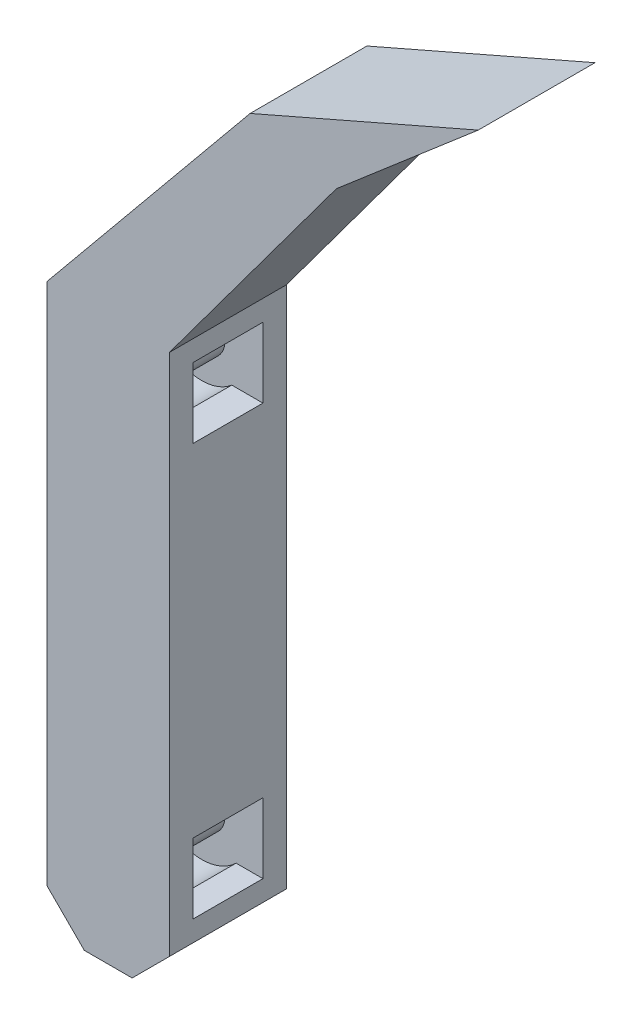
SolidWorks part; units mm, degrees
ref_plane "前视基准面" through (0, 0, 0) normal (0, 0, 1) x (1, 0, 0)
ref_plane "上视基准面" through (0, 0, 0) normal (0, 1, 0) x (1, 0, 0)
ref_plane "右视基准面" through (0, 0, 0) normal (1, 0, 0) x (0, 0, -1)
sketch "草图1" plane through (0, 0, 0) normal (0, 0, 1) x (1, 0, 0)
  line L0 (-9.5511, 87.4533) -> (33.9443, 140.3649)
  line L1 (-9.5511, 87.4533) -> (16.6885, 87.4533)
  line L2 (-9.5511, 87.4533) -> (-9.5511, -32.5467)
  line L3 (-9.5511, -32.5467) -> (16.6885, -32.5467)
  line L4 (16.6885, 87.4533) -> (16.6885, -32.5467)
  line L7 (33.9443, 140.3649) -> (82.784, 161.6933)
  line L8 (82.784, 161.6933) -> (52.4218, 135.6522)
  line L9 (52.4218, 135.6522) -> (16.6885, 87.4533)
  point P0 (0, 0)
  point P5 (0, 0)
  point P10 (0, 0)
  point P11 (82.784, 161.6933)
  point P12 (-84.1725, 179.7601)
  dimension "D1" = 120
  dimension "D2" = 60
  dimension "D3" = 40
extrude "凸台-拉伸1" add sketch "草图1" along normal blind 25 contours L4 L1 L2 L3 | L9 L8 L7 L0 L1
chamfer "倒角1" distance 8 angle 45 2 edges at (16.6885, -32.5467, 12.5) (-9.5511, -32.5467, 12.5)
sketch "草图3" plane through (-9.5511, 0, 0) normal (-1, 0, 0) x (0, 0, 1)
  line L1 (5, -5.1272) -> (20, -5.1272)
  line L2 (5, -5.1272) -> (5, -20.1272)
  line L3 (5, -20.1272) -> (20, -20.1272)
  line L4 (20, -5.1272) -> (20, -20.1272)
  line L5 (5, -5.1272) -> (20, -20.1272) construction
  line L6 (5, -20.1272) -> (20, -5.1272) construction
extrude "切除-拉伸4" cut sketch "草图3" against normal blind 35
sketch "草图4" plane through (0, 0, 5) normal (0, 0, 1) x (1, 0, 0)
  line L0 (-9.5511, -5.1272) -> (16.6885, -20.1272)
  line L1 (16.6885, -5.1272) -> (-9.5511, -20.1272)
  line L4 (16.6885, -20.1272) -> (16.6885, -5.1272)
  line L5 (16.6885, -5.1272) -> (-9.5511, -5.1272)
  line L6 (-9.5511, -5.1272) -> (-9.5511, -20.1272)
  line L7 (-9.5511, -20.1272) -> (16.6885, -20.1272)
  line L8 (16.6885, -20.1272) -> (16.6885, -5.1272)
  line L9 (16.6885, -5.1272) -> (-9.5511, -5.1272)
  line L10 (-9.5511, -5.1272) -> (-9.5511, -20.1272)
  line L11 (-9.5511, -20.1272) -> (16.6885, -20.1272)
  circle A0 centre (3.5687, -12.6272) radius 5
  dimension "D2" = 10
  dimension "D1" = 0
extrude "凸台-拉伸2" add sketch "草图4" along normal blind 15 contours A0
sketch "草图5" plane through (0, 0, 5) normal (0, 0, 1) x (1, 0, 0)
  circle A0 centre (3.5687, -12.6272) radius 5 construction
  circle A1 centre (3.5687, -12.6272) radius 5
  circle A2 centre (3.5687, -12.6272) radius 10.5135
extrude "切除-拉伸5" cut sketch "草图5" along normal blind 15
sketch "草图6" plane through (-9.5511, 0, 0) normal (-1, 0, 0) x (0, 0, 1)
  line L0 (5, -5.1272) -> (5, -20.1272) construction
  line L1 (20, -20.1272) -> (20, -5.1272) construction
  line L2 (20, -5.1272) -> (5, -5.1272) construction
  line L3 (5, -5.1272) -> (5, -20.1272)
  line L4 (0, 87.4533) -> (0, -24.5467)
  line L5 (0, -24.5467) -> (25, -24.5467)
  line L6 (25, -24.5467) -> (25, 87.4533)
  line L7 (25, 87.4533) -> (0, 87.4533)
  line L8 (0, 87.4533) -> (0, -24.5467)
  line L9 (0, -24.5467) -> (25, -24.5467)
  line L10 (25, -24.5467) -> (25, 87.4533)
  line L11 (25, 87.4533) -> (0, 87.4533)
  line L12 (20, -20.1272) -> (20, -5.1272)
  line L13 (20, -5.1272) -> (5, -5.1272)
  line L14 (5, -20.1272) -> (20, -20.1272) construction
  line L15 (5, -20.1272) -> (20, -20.1272)
  line L16 (25, 31.4533) -> (0, 31.4533)
  line L17 (5, 83.0339) -> (20, 83.0339)
  line L18 (5, 68.0339) -> (5, 83.0339)
  line L19 (20, 83.0339) -> (20, 68.0339)
  line L20 (20, 68.0339) -> (5, 68.0339)
  dimension "D1" = 0
extrude "切除-拉伸6" cut sketch "草图6" against normal through all contours L20 L19 L17 L18
sketch "草图7" plane through (0, 0, 5) normal (0, 0, 1) x (1, 0, 0)
  circle A0 centre (3.5687, 75.5339) radius 5
  dimension "D2" = 10
extrude "凸台-拉伸3" add sketch "草图7" along normal blind 15
sketch "草图8" plane through (0, 0, 5) normal (0, 0, 1) x (1, 0, 0)
  line L4 (16.6885, 83.0339) -> (-9.5511, 83.0339)
  line L5 (-9.5511, 83.0339) -> (-9.5511, 68.0339)
  line L6 (-9.5511, 68.0339) -> (16.6885, 68.0339)
  line L7 (16.6885, 68.0339) -> (16.6885, 83.0339)
  line L8 (16.6885, 83.0339) -> (-9.5511, 83.0339)
  line L9 (-9.5511, 83.0339) -> (-9.5511, 68.0339)
  line L10 (-9.5511, 68.0339) -> (16.6885, 68.0339)
  line L11 (16.6885, 68.0339) -> (16.6885, 83.0339)
  circle A0 centre (3.5687, 75.5339) radius 5 construction
  circle A1 centre (3.5687, 75.5339) radius 5
  circle A2 centre (3.5687, 75.5339) radius 9.8908
  circle M6 centre (3.5687, 75.5339) radius 5
  dimension "D1" = 0
extrude "切除-拉伸9" cut sketch "草图8" along normal blind 15 contours L8 A2 L10 M6 | L8 A2 | L10 A2
